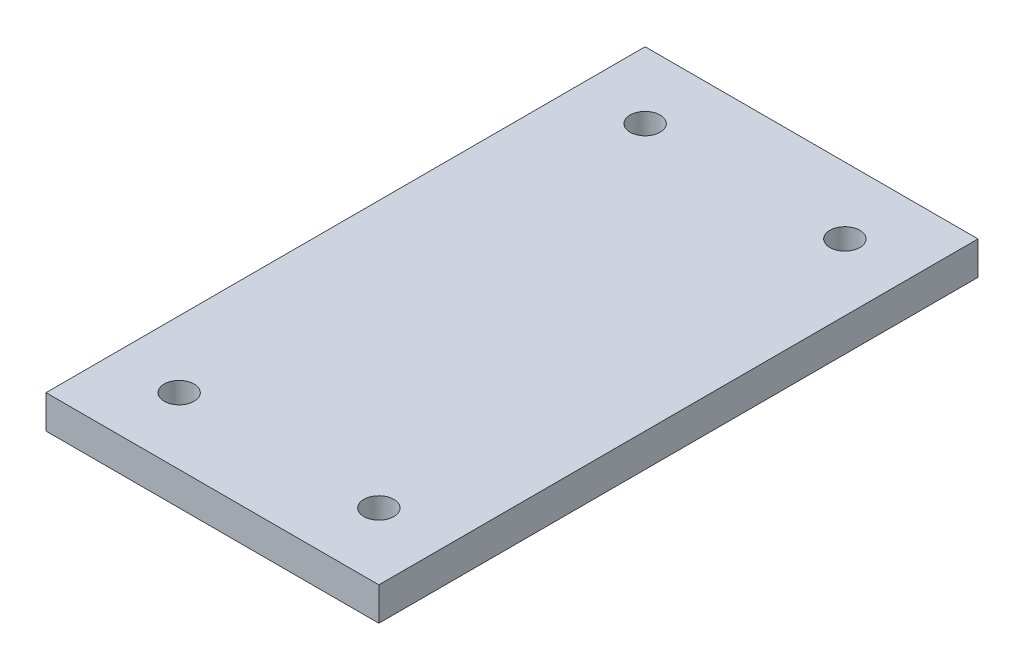
SolidWorks part; units mm, degrees
ref_plane "Front Plane" through (0, 0, 0) normal (0, 0, 1) x (1, 0, 0)
ref_plane "Top Plane" through (0, 0, 0) normal (0, 1, 0) x (1, 0, 0)
ref_plane "Right Plane" through (0, 0, 0) normal (1, 0, 0) x (0, 0, -1)
sketch "Sketch1" plane through (0, 0, 0) normal (0, 1, 0) x (1, 0, 0)
  line L0 (0, 0) -> (-29.6492, 0) construction
  line L1 (0, 0) -> (0, -12.8779) construction
  line L3 (25, -45) -> (-25, -45)
  line L4 (25, -45) -> (25, 45)
  line L5 (25, 45) -> (-25, 45)
  line L6 (-25, -45) -> (-25, 45)
  line L7 (25, -45) -> (-25, 45) construction
  line L8 (25, 45) -> (-25, -45) construction
  circle A0 centre (15, 35) radius 2.25
  circle A1 centre (15, -35) radius 2.25
  circle A2 centre (-15, -35) radius 2.25
  circle A3 centre (-15, 35) radius 2.25
  point P13 (0, 0)
  dimension "D1" = 4.5
  dimension "D4" = 10
  dimension "D5" = 10
  dimension "D2" = 35
  dimension "D3" = 15
extrude "Boss-Extrude1" add sketch "Sketch1" along normal mid plane 5
sketch "Sketch2" plane through (0, 2.5, 0) normal (0, 1, 0) x (1, 0, 0)
  line L4 (-25, 45) -> (-25, -45)
  line L5 (-25, -45) -> (25, -45)
  line L6 (25, -45) -> (25, 45)
  line L7 (25, 45) -> (-25, 45)
  line L8 (-25, 45) -> (-25, -45)
  line L9 (-25, -45) -> (25, -45)
  line L10 (25, -45) -> (25, 45)
  line L11 (25, 45) -> (-25, 45)
  circle A0 centre (-15, -35) radius 2.25 construction
  circle A1 centre (15, -35) radius 2.25 construction
  circle A2 centre (15, 35) radius 2.25 construction
  circle A3 centre (-15, 35) radius 2.25 construction
  circle A4 centre (-15, -35) radius 2.25
  circle A5 centre (15, -35) radius 2.25
  circle A6 centre (15, 35) radius 2.25
  circle A7 centre (-15, 35) radius 2.25
  point P19 (-25, -30.1118)
  point P20 (-16.7157, -31.6901)
  dimension "D2" = 70
  dimension "D3" = 10
  dimension "D4" = 15
  dimension "D5" = 10
  dimension "D6" = 90
  dimension "D7" = 50
  dimension "D8" = 25
  dimension "D9" = 10
  dimension "D1" = 0
